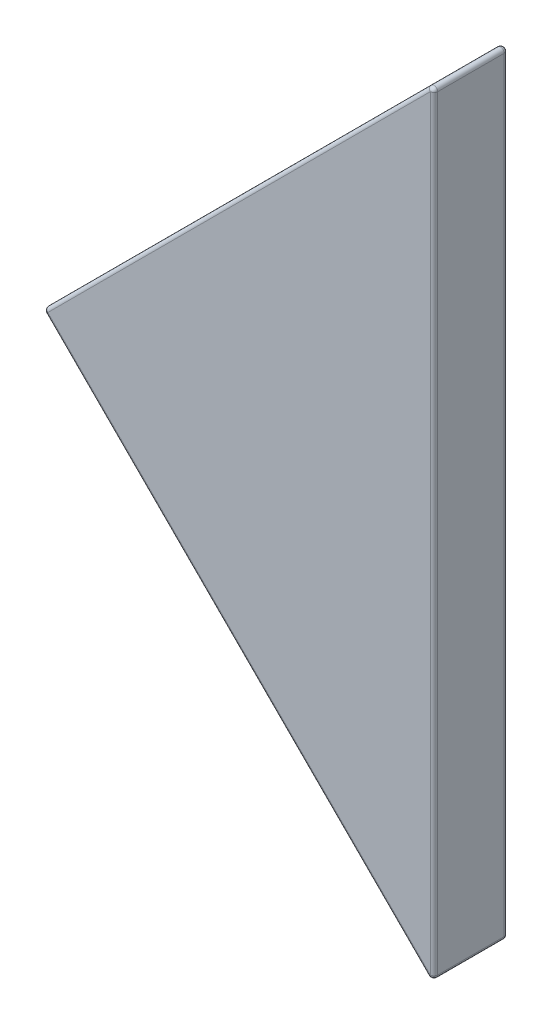
SolidWorks part; units mm, degrees
ref_plane "前视基准面" through (0, 0, 0) normal (0, 0, 1) x (1, 0, 0)
ref_plane "上视基准面" through (0, 0, 0) normal (0, 1, 0) x (1, 0, 0)
ref_plane "右视基准面" through (0, 0, 0) normal (1, 0, 0) x (0, 0, -1)
sketch "草图1" plane through (0, 0, 0) normal (0, 0, 1) x (1, 0, 0)
  line L35 (0, 0) -> (0, 106.066)
  line L36 (-53.033, 53.033) -> (0, 106.066)
  line L37 (-53.033, 53.033) -> (0, 0)
  dimension "D1" = 75
  dimension "D2" = 45
extrude "凸台-拉伸1" add sketch "草图1" along normal blind 10
fillet "圆角1" radius 0.5 9 edges at (-53.033, 53.033, 5) (0, 0, 5) (0, 106.066, 5) (0, 53.033, 10) (-26.5165, 26.5165, 10) (-26.5165, 79.5495, 10) (0, 53.033, 0) (-26.5165, 26.5165, 0) (-26.5165, 79.5495, 0)
